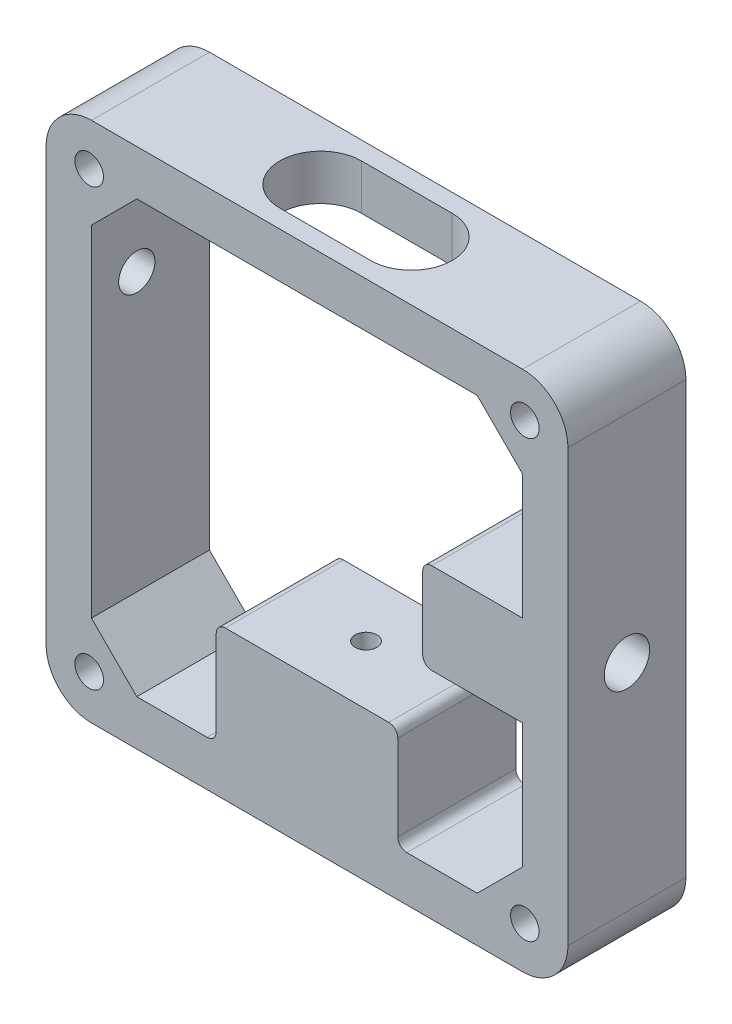
SolidWorks part; units mm, degrees
ref_plane "Front Plane" through (0, 0, 0) normal (0, 0, 1) x (1, 0, 0)
ref_plane "Top Plane" through (0, 0, 0) normal (0, 1, 0) x (1, 0, 0)
ref_plane "Right Plane" through (0, 0, 0) normal (1, 0, 0) x (0, 0, -1)
ref_plane "Plane1" through (0, -24.638, 0) normal (0, 1, 0) x (1, 0, 0)
ref_plane "Plane2" through (0, 0, -13) normal (0, 0, 1) x (1, 0, 0)
sketch "Sketch1" plane through (0, 0, -13) normal (0, 0, 1) x (1, 0, 0)
  line L1 (57.5, 57.5) -> (-57.5, 57.5)
  line L2 (57.5, 57.5) -> (57.5, -57.5)
  line L3 (57.5, -57.5) -> (-57.5, -57.5)
  line L4 (-57.5, 57.5) -> (-57.5, -57.5)
  line L5 (57.5, 57.5) -> (-57.5, -57.5) construction
  line L6 (57.5, -57.5) -> (-57.5, 57.5) construction
  line L7 (47.5, -47.5) -> (-47.5, -47.5)
  line L8 (47.5, -47.5) -> (47.5, 47.5)
  line L9 (47.5, 47.5) -> (-47.5, 47.5)
  line L10 (-47.5, -47.5) -> (-47.5, 47.5)
  line L11 (47.5, -47.5) -> (-47.5, 47.5) construction
  line L12 (47.5, 47.5) -> (-47.5, -47.5) construction
  point P0 (0, 0)
  point P6 (0, 0)
  dimension "D1" = 115
  dimension "D2" = 115
  dimension "D3" = 95
  dimension "D4" = 95
extrude "Boss-Extrude1" add sketch "Sketch1" along normal blind 26
sketch "Sketch10" plane through (0, -24.638, 0) normal (0, 1, 0) x (1, 0, 0)
  line L0 (57.5, 13) -> (-57.5, 13) construction
  line L1 (20, -13) -> (-20, -13)
  line L2 (20, -13) -> (20, 13)
  line L3 (20, 13) -> (-20, 13)
  line L4 (-20, -13) -> (-20, 13)
  line L5 (20, -13) -> (-20, 13) construction
  line L6 (20, 13) -> (-20, -13) construction
  point P0 (0, 0)
  dimension "D1" = 40
extrude "Boss-Extrude4" add sketch "Sketch10" against normal blind 27
ref_plane "Plane3" through (0, -57.5, 0) normal (0, -1, 0) x (-1, 0, 0)
sketch "Sketch3" plane through (0, -57.5, 0) normal (0, -1, 0) x (-1, 0, 0)
  line L1 (7.5, -7.5) -> (-7.5, -7.5)
  line L2 (7.5, -7.5) -> (7.5, 7.5)
  line L3 (7.5, 7.5) -> (-7.5, 7.5)
  line L4 (-7.5, -7.5) -> (-7.5, 7.5)
  line L5 (7.5, -7.5) -> (-7.5, 7.5) construction
  line L6 (7.5, 7.5) -> (-7.5, -7.5) construction
  point P0 (0, 0)
  dimension "D1" = 15
  dimension "D2" = 15
extrude "Cut-Extrude1" cut sketch "Sketch3" against normal blind 24
fillet "Fillet1" radius 10 4 edges at (-57.5, -57.5, 0) (57.5, -57.5, 0) (57.5, 57.5, 0) (-57.5, 57.5, 0)
chamfer "Chamfer1" distance 10 angle 45 4 edges at (47.5, -47.5, 0) (-47.5, -47.5, 0) (47.5, 47.5, 0) (-47.5, 47.5, 0)
sketch "Sketch4" plane through (0, 0, 0) normal (0, 0, 1) x (1, 0, 0)
  line L0 (0, -14.3) -> (0, 14.3) construction
  line L1 (14.3, 0) -> (-14.3, 0) construction
  circle A0 centre (-48, 48) radius 3.15
  circle A1 centre (48, 48) radius 3.15
  circle A2 centre (48, -48) radius 3.15
  circle A3 centre (-48, -48) radius 3.15
  dimension "D1" = 6.3
  dimension "D2" = 48
  dimension "D3" = 48
extrude "Cut-Extrude3" cut sketch "Sketch4" against normal mid plane 115
sketch "Sketch5" plane through (0, 0, 0) normal (0, 0, 1) x (1, 0, 0)
  line L5 (47.5, 9.9765) -> (47.5, -10.0235)
  line L6 (47.5, 9.9765) -> (22.5, 9.9765)
  line L7 (47.5, -10.0235) -> (22.5, -10.0235)
  line L8 (22.5, 9.9765) -> (22.5, -10.0235)
  line L9 (47.5, -37.5) -> (47.5, 37.5) construction
  dimension "D1" = 20
  dimension "D2" = 25
extrude "Boss-Extrude3" [suppressed] add sketch "Sketch5" along normal mid plane 20
ref_plane "Plane4" through (0, 0, 13) normal (0, 0, 1) x (1, 0, 0)
sketch "Sketch6" plane through (0, 0, 13) normal (0, 0, 1) x (1, 0, 0)
  line L1 (21, 15) -> (-21, 15)
  line L2 (21, 15) -> (21, -15)
  line L3 (21, -15) -> (-21, -15)
  line L4 (-21, 15) -> (-21, -15)
  line L5 (21, 15) -> (-21, -15) construction
  line L6 (21, -15) -> (-21, 15) construction
  point P0 (0, 0)
  dimension "D1" = 42
  dimension "D2" = 30
extrude "Cut-Extrude4" [suppressed] cut sketch "Sketch6" against normal blind 30
ref_plane "Plane5" through (57.5, 0, 0) normal (1, 0, 0) x (0, 0, -1)
sketch "Sketch7" plane through (57.5, 0, 0) normal (1, 0, 0) x (0, 0, -1)
  circle A0 centre (30, 0) radius 25
  dimension "D2" = 50
  dimension "D1" = 30
extrude "Cut-Extrude5" [suppressed] cut sketch "Sketch7" against normal through all
sketch "Sketch8" plane through (57.5, 0, 0) normal (1, 0, 0) x (0, 0, -1)
  line L1 (5, 10) -> (25, 10)
  line L2 (5, 10) -> (5, -10)
  line L3 (5, -10) -> (25, -10)
  line L4 (25, 10) -> (25, -10)
  line L5 (5, 10) -> (25, -10) construction
  line L6 (5, -10) -> (25, 10) construction
  point P0 (15, 0)
  dimension "D1" = 15
  dimension "D2" = 20
  dimension "D3" = 20
extrude "Cut-Extrude6" [suppressed] cut sketch "Sketch8" against normal through all
fillet "Fillet3" [suppressed] radius 2
ref_plane "Plane6" through (-57.5, 0, 0) normal (-1, 0, 0) x (0, 0, 1)
sketch "Sketch9" plane through (-57.5, 0, 0) normal (-1, 0, 0) x (0, 0, 1)
  circle A0 centre (3, 23.6) radius 4
  dimension "D1" = 8
  dimension "D2" = 3
  dimension "D3" = 23.6
extrude "Cut-Extrude7" cut sketch "Sketch9" against normal blind 30
fillet "Fillet4" [suppressed] radius 2
fillet "Fillet5" radius 2 4 edges at (-20, -47.5, 0) (20, -47.5, 0) (20, -24.638, 0) (-20, -24.638, 0)
ref_plane "Plane7" through (25.5, 0, 0) normal (1, 0, 0) x (0, 0, -1)
sketch "Sketch11" plane through (25.5, 0, 0) normal (1, 0, 0) x (0, 0, -1)
  line L0 (-13, -47.5) -> (-13, 47.5) construction
  line L1 (13, -10) -> (-13, -10)
  line L2 (13, -10) -> (13, 10)
  line L3 (13, 10) -> (-13, 10)
  line L4 (-13, -10) -> (-13, 10)
  line L5 (13, -10) -> (-13, 10) construction
  line L6 (13, 10) -> (-13, -10) construction
  point P0 (0, 0)
  dimension "D1" = 20
extrude "Boss-Extrude5" add sketch "Sketch11" along normal blind 25
fillet "Fillet6" radius 2 2 edges at (25.5, -10, 0) (25.5, 10, 0)
ref_plane "Plane8" through (57.5, 0, 0) normal (1, 0, 0) x (0, 0, -1)
sketch "Sketch13" plane through (57.5, 0, 0) normal (1, 0, 0) x (0, 0, -1)
  circle A0 centre (0, 0) radius 5
  dimension "D1" = 10
extrude "Cut-Extrude9" cut sketch "Sketch13" against normal blind 25
sketch "Sketch14" plane through (25.5, 0, 0) normal (1, 0, 0) x (0, 0, -1)
  circle A0 centre (0, 0) radius 2.5
  dimension "D1" = 5
extrude "Cut-Extrude10" cut sketch "Sketch14" along normal blind 15
ref_plane "Plane9" through (0, 57.5, 0) normal (0, 1, 0) x (1, 0, 0)
sketch "Sketch15" plane through (0, 57.5, 0) normal (0, 1, 0) x (1, 0, 0)
  line L0 (-10, 0) -> (10, 0) construction
  line L1 (-10, 9) -> (10, 9)
  line L2 (-10, -9) -> (10, -9)
  arc A0 (-10, 9) -> (-10, -9) centre (-10, 0) ccw
  arc A1 (10, -9) -> (10, 9) centre (10, 0) ccw
  point P2 (0, 0)
  dimension "D2" = 9
  dimension "D1" = 20
extrude "Cut-Extrude11" cut sketch "Sketch15" against normal blind 10
ref_plane "Plane10" through (0, -24.638, 0) normal (0, 1, 0) x (1, 0, 0)
sketch "Sketch16" plane through (0, -24.638, 0) normal (0, 1, 0) x (1, 0, 0)
  circle A0 centre (0, 0) radius 2.4
  dimension "D1" = 4.8
extrude "Cut-Extrude12" cut sketch "Sketch16" against normal blind 30
